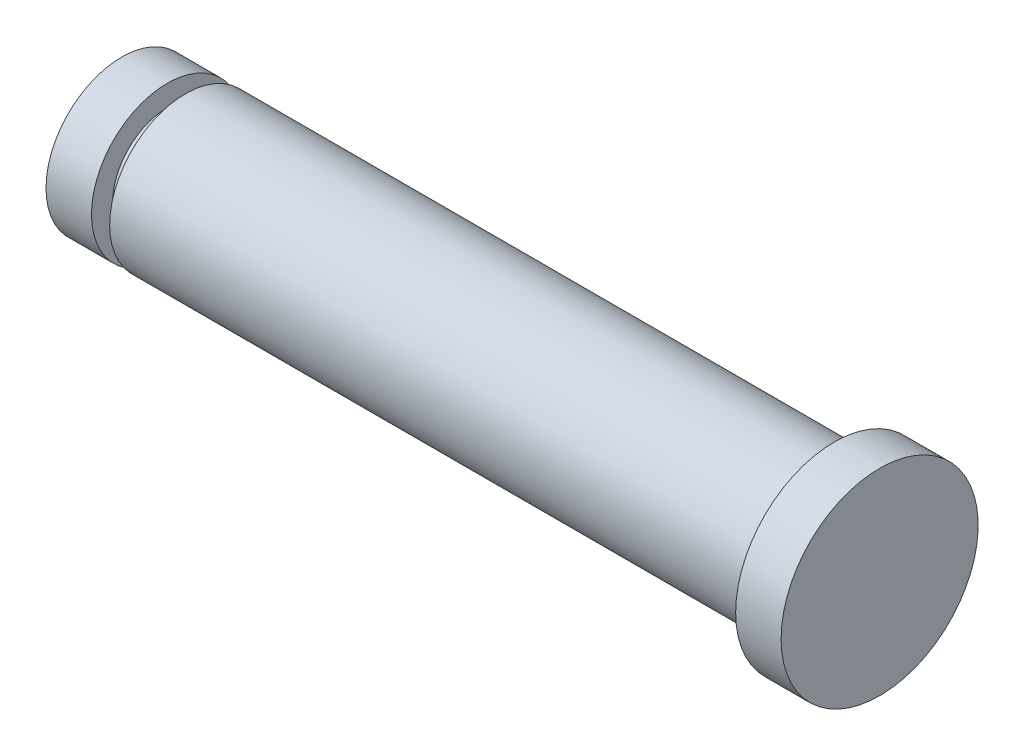
SolidWorks part; units mm, degrees
ref_plane "前视" through (0, 0, 0) normal (0, 0, 1) x (1, 0, 0)
ref_plane "上视" through (0, 0, 0) normal (0, 1, 0) x (1, 0, 0)
ref_plane "右视" through (0, 0, 0) normal (1, 0, 0) x (0, 0, -1)
sketch "草图1" plane through (0, 0, 0) normal (0, 0, 1) x (1, 0, 0)
  line L0 (0, 0) -> (250, 0)
  line L1 (21, 25) -> (235, 25)
  line L2 (235, 25) -> (235, 32.5)
  line L3 (235, 32.5) -> (250, 32.5)
  line L4 (250, 32.5) -> (250, 0)
  line L5 (21, 25) -> (21, 18)
  line L6 (21, 18) -> (15, 18)
  line L7 (15, 18) -> (15, 25)
  line L8 (15, 25) -> (0, 25)
  line L9 (0, 25) -> (0, 0)
  dimension "D1" = 250
  dimension "D2" = 214
  dimension "D3" = 25
  dimension "D4" = 15
  dimension "D5" = 32.5
  dimension "D6" = 6
  dimension "D7" = 18
revolve "旋转1" add sketch "草图1" angle 360 about L0
